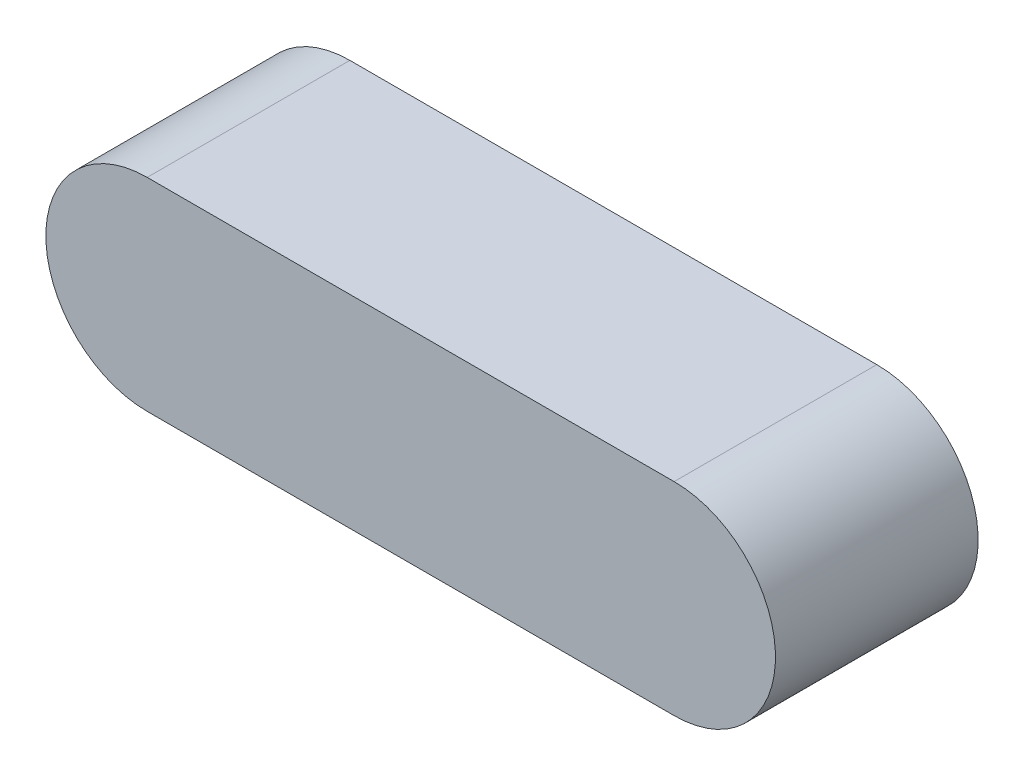
SolidWorks part; units mm, degrees
ref_plane "Plan de face" through (0, 0, 0) normal (0, 0, 1) x (1, 0, 0)
ref_plane "Plan de dessus" through (0, 0, 0) normal (0, 1, 0) x (1, 0, 0)
ref_plane "Plan de droite" through (0, 0, 0) normal (1, 0, 0) x (0, 0, -1)
sketch "Esquisse1" plane through (0, 0, 0) normal (0, 0, 1) x (1, 0, 0)
  line L0 (0, 0) -> (13, 0)
  line L1 (13, -5) -> (0, -5)
  arc A0 (13, 0) -> (13, -5) centre (13, -2.5) cw
  arc A1 (0, -5) -> (0, 0) centre (0, -2.5) cw
  dimension "D1" = 5
  dimension "D2" = 13
extrude "Extrusion1" add sketch "Esquisse1" along normal blind 5
